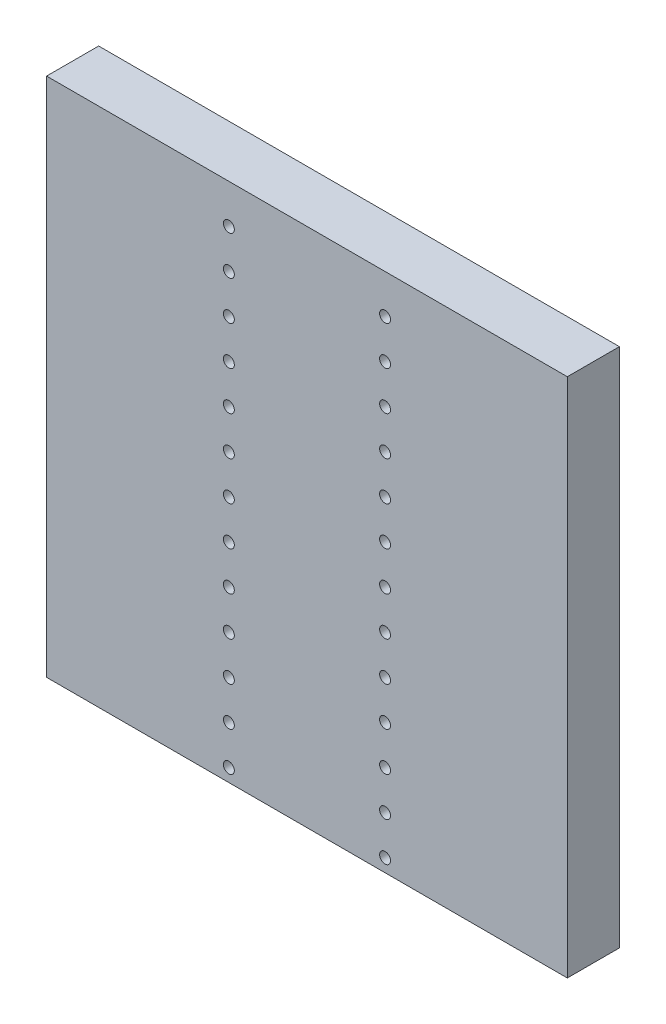
SolidWorks part; units mm, degrees
ref_plane "Front Plane" through (0, 0, 0) normal (0, 0, 1) x (1, 0, 0)
ref_plane "Top Plane" through (0, 0, 0) normal (0, 1, 0) x (1, 0, 0)
ref_plane "Right Plane" through (0, 0, 0) normal (1, 0, 0) x (0, 0, -1)
sketch "Sketch1" plane through (0, 0, 0) normal (0, 0, 1) x (1, 0, 0)
  line L1 (-100, 100) -> (100, 100)
  line L2 (-100, 100) -> (-100, -100)
  line L3 (-100, -100) -> (100, -100)
  line L4 (100, 100) -> (100, -100)
  line L5 (-100, 100) -> (100, -100) construction
  line L6 (-100, -100) -> (100, 100) construction
  point P0 (0, 0)
  dimension "D1" = 200
  dimension "D2" = 200
extrude "Boss-Extrude1" add sketch "Sketch1" along normal blind 20
sketch "Sketch2" plane through (0, 0, 20) normal (0, 0, 1) x (1, 0, 0)
  line L0 (30, 100) -> (30, -100) construction
  line L1 (100, 100) -> (-100, 100) construction
  line L2 (-100, -100) -> (100, -100) construction
  line L3 (100, -100) -> (100, 100) construction
  circle A0 centre (30, -95) radius 2.1
  point P10 (0, 0)
  dimension "D2" = 4.2
  dimension "D1" = 70
  dimension "D3" = 5
hole_wizard "M5x0.8 Tapped Hole1" positions "3DSketch1" profile "Sketch3" tap size "M5x0.8" standard "ANSI Metric" end condition up to next
sketch3d "3DSketch1"
  point P0 (30, -95, 20)
sketch "Sketch3" plane through (30, -95, 20) normal (1, 0, 0) x (0, -1, 0)
  line L0 (0, 0) -> (0, 20)
  line L1 (0, 20) -> (2.1, 20)
  line L2 (2.1, 20) -> (2.1, 0)
  line L5 (2.1, 0) -> (0, 0)
  line L11 (0, -6.35) -> (0, 107.95) construction
  dimension "Thru Tap Drill Dia." = 4.2
  dimension "Thru Tap Drill Depth" = 20
cosmetic thread "Hole Thread1" parameters "D2"=5
pattern_linear "LPattern1" count 13 spacing 15 along (0, 1, 0) of "M5x0.8 Tapped Hole1"
cosmetic thread "Hole Thread2" parameters "D1"=10, "D2"=5
cosmetic thread "Hole Thread3" parameters "D1"=10, "D2"=5
cosmetic thread "Hole Thread4" parameters "D1"=10, "D2"=5
cosmetic thread "Hole Thread5" parameters "D1"=10, "D2"=5
cosmetic thread "Hole Thread6" parameters "D1"=10, "D2"=5
cosmetic thread "Hole Thread7" parameters "D1"=10, "D2"=5
cosmetic thread "Hole Thread8" parameters "D1"=10, "D2"=5
cosmetic thread "Hole Thread9" parameters "D1"=10, "D2"=5
cosmetic thread "Hole Thread10" parameters "D1"=10, "D2"=5
cosmetic thread "Hole Thread11" parameters "D1"=10, "D2"=5
cosmetic thread "Hole Thread12" parameters "D1"=10, "D2"=5
cosmetic thread "Hole Thread13" parameters "D1"=10, "D2"=5
mirror "Mirror1" about plane through (0, 0, 0) normal (1, 0, 0) of "LPattern1", "M5x0.8 Tapped Hole1"
cosmetic thread "Hole Thread14" parameters "D1"=10, "D2"=5
cosmetic thread "Hole Thread15" parameters "D1"=10, "D2"=5
cosmetic thread "Hole Thread16" parameters "D1"=10, "D2"=5
cosmetic thread "Hole Thread17" parameters "D1"=10, "D2"=5
cosmetic thread "Hole Thread18" parameters "D1"=10, "D2"=5
cosmetic thread "Hole Thread19" parameters "D1"=10, "D2"=5
cosmetic thread "Hole Thread20" parameters "D1"=10, "D2"=5
cosmetic thread "Hole Thread21" parameters "D1"=10, "D2"=5
cosmetic thread "Hole Thread22" parameters "D1"=10, "D2"=5
cosmetic thread "Hole Thread23" parameters "D1"=10, "D2"=5
cosmetic thread "Hole Thread24" parameters "D1"=10, "D2"=5
cosmetic thread "Hole Thread25" parameters "D1"=10, "D2"=5
cosmetic thread "Hole Thread26" parameters "D1"=10, "D2"=5
